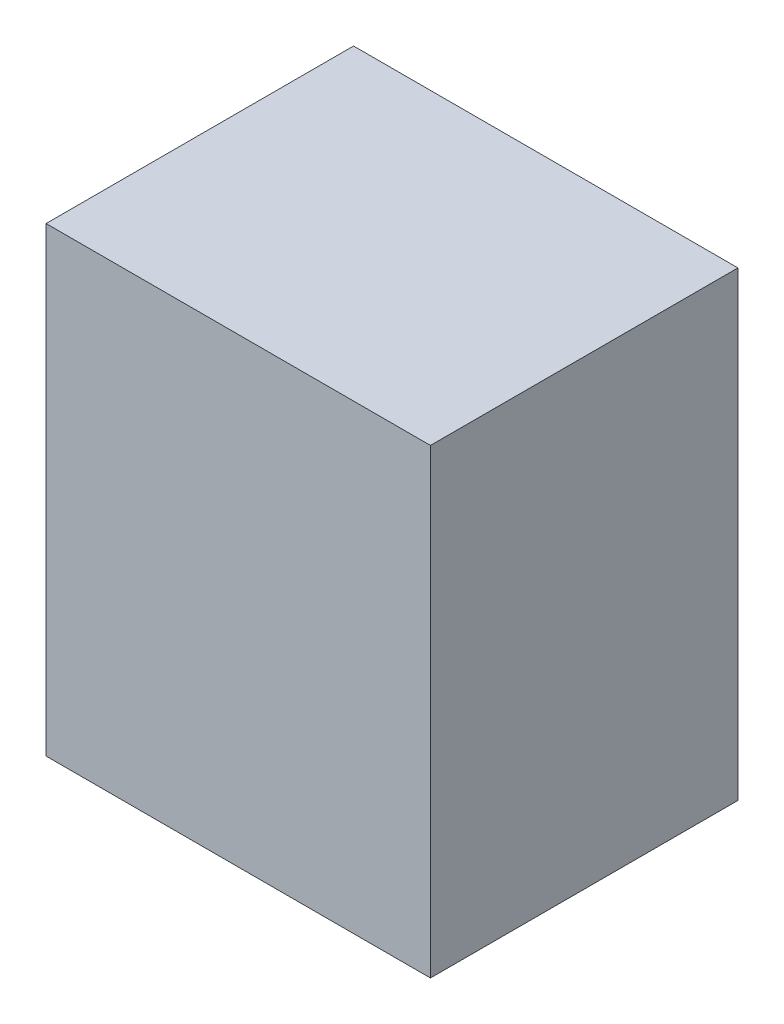
SolidWorks part; units mm, degrees
ref_plane "Front Plane" through (0, 0, 0) normal (0, 0, 1) x (1, 0, 0)
ref_plane "Top Plane" through (0, 0, 0) normal (0, 1, 0) x (1, 0, 0)
ref_plane "Right Plane" through (0, 0, 0) normal (1, 0, 0) x (0, 0, -1)
sketch "Sketch1" plane through (0, 0, 0) normal (0, 1, 0) x (1, 0, 0)
  line L1 (0, 0) -> (111.125, 0)
  line L2 (0, 0) -> (0, 88.9)
  line L3 (0, 88.9) -> (111.125, 88.9)
  line L4 (111.125, 0) -> (111.125, 88.9)
  dimension "D1" = 111.125
  dimension "D2" = 88.9
extrude "Boss-Extrude1" add sketch "Sketch1" along normal blind 133.35
